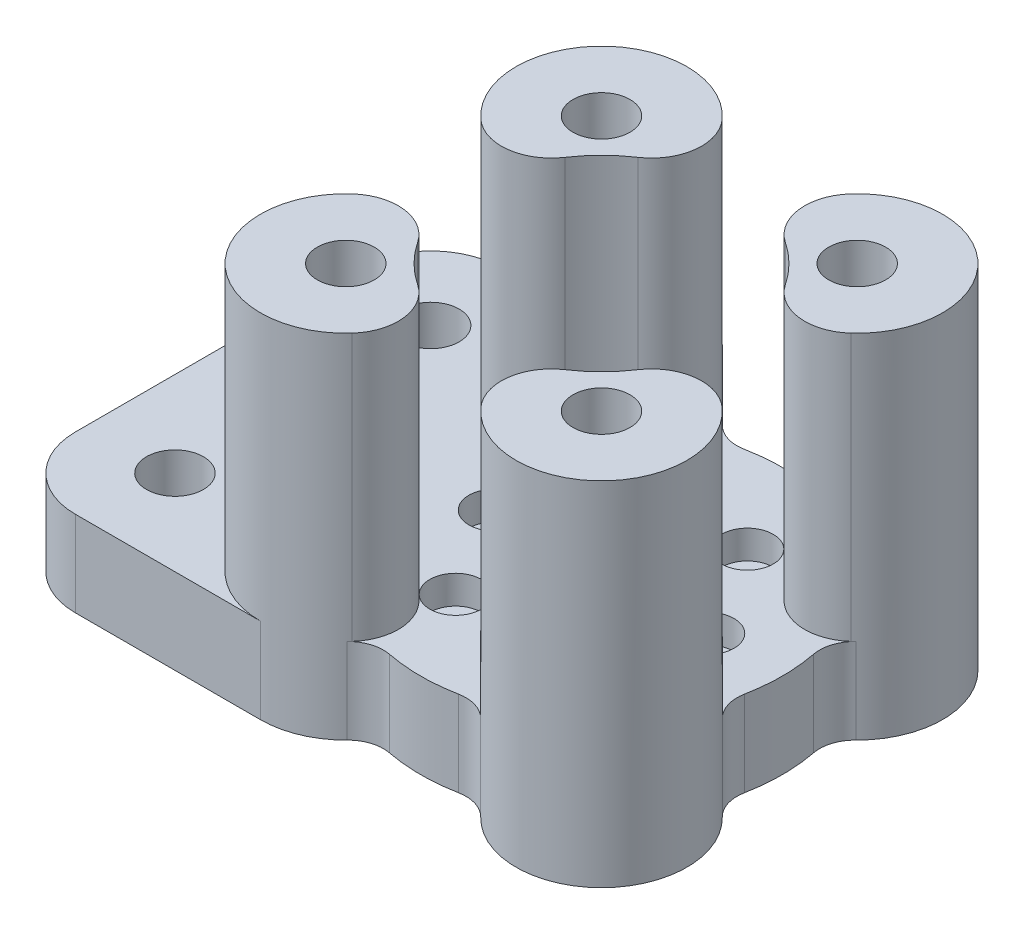
SolidWorks part; units mm, degrees
material "1060 Alloy"
ref_plane "Front" through (0, 0, 0) normal (0, 0, 1) x (1, 0, 0)
ref_plane "Top" through (0, 0, 0) normal (0, 1, 0) x (1, 0, 0)
ref_plane "Right" through (0, 0, 0) normal (1, 0, 0) x (0, 0, -1)
sketch "Sketch1" plane through (0, 0, 0) normal (0, 1, 0) x (1, 0, 0)
  line L0 (0, 0) -> (-17.9605, 17.9605) construction
  line L1 (0, 0) -> (0, 25.4) construction
  line L2 (0, 0) -> (-7.5, 12.9904) construction
  line L3 (-17.9605, 29.9605) -> (-43.9605, 29.9605)
  line L4 (-53.9605, 19.9605) -> (-53.9605, -19.9605)
  line L5 (-43.9605, -29.9605) -> (-17.9605, -29.9605)
  circle A0 centre (-17.9605, 17.9605) radius 4
  circle A1 centre (17.9605, 17.9605) radius 4
  circle A2 centre (17.9605, -17.9605) radius 4
  circle A3 centre (-17.9605, -17.9605) radius 4
  circle A4 centre (0, 0) radius 10.5
  arc A5 (-9.3775, 26.347) -> (-26.347, 9.3775) centre (-17.9605, 17.9605) ccw construction
  arc A6 (26.347, 9.3775) -> (9.3775, 26.347) centre (17.9605, 17.9605) ccw
  arc A7 (9.3775, -26.347) -> (26.347, -9.3775) centre (17.9605, -17.9605) ccw
  arc A8 (-26.347, -9.3775) -> (-9.3775, -26.347) centre (-17.9605, -17.9605) ccw construction
  arc A9 (-24.9332, 4.8471) -> (-24.9332, -4.8471) centre (0, 0) ccw construction
  arc A10 (-4.8471, -24.9332) -> (4.8471, -24.9332) centre (0, 0) ccw
  arc A11 (24.9332, -4.8471) -> (24.9332, 4.8471) centre (0, 0) ccw
  arc A12 (-4.8471, 24.9332) -> (-9.3775, 26.347) centre (-5.8013, 29.8413) cw
  arc A13 (4.8471, 24.9332) -> (-4.8471, 24.9332) centre (0, 0) ccw
  arc A14 (9.3775, 26.347) -> (4.8471, 24.9332) centre (5.8013, 29.8413) cw
  arc A15 (26.347, 9.3775) -> (24.9332, 4.8471) centre (29.8413, 5.8013) ccw
  arc A16 (24.9332, -4.8471) -> (26.347, -9.3775) centre (29.8413, -5.8013) ccw
  arc A17 (9.3775, -26.347) -> (4.8471, -24.9332) centre (5.8013, -29.8413) ccw
  arc A18 (-4.8471, -24.9332) -> (-9.3775, -26.347) centre (-5.8013, -29.8413) ccw
  arc A19 (-24.9332, -4.8471) -> (-26.347, -9.3775) centre (-29.8413, -5.8013) cw construction
  arc A20 (-24.9332, 4.8471) -> (-26.347, 9.3775) centre (-29.8413, 5.8013) ccw construction
  circle A21 centre (0, 0) radius 15 construction
  circle A22 centre (-7.5, 12.9904) radius 2
  circle A23 centre (7.5, 12.9904) radius 2
  circle A24 centre (15, 0) radius 2
  circle A25 centre (7.5, -12.9904) radius 2
  circle A26 centre (-7.5, -12.9904) radius 2
  circle A27 centre (-15, 0) radius 2
  arc A28 (-9.3775, 26.347) -> (-17.9605, 29.9605) centre (-17.9605, 17.9605) ccw
  arc A29 (-9.3775, -26.347) -> (-17.9605, -29.9605) centre (-17.9605, -17.9605) cw
  circle A30 centre (-41.9605, 17.9605) radius 4
  circle A31 centre (-41.9605, -17.9605) radius 4
  arc A32 (-53.9605, -19.9605) -> (-43.9605, -29.9605) centre (-43.9605, -19.9605) ccw
  arc A33 (-43.9605, 29.9605) -> (-53.9605, 19.9605) centre (-43.9605, 19.9605) ccw
  point P0 (0, 0)
  point P17 (0, 0)
  point P27 (0, 0)
  point P56 (0, 0)
  dimension "D5" = 8
  dimension "D6" = 21
  dimension "D1" = 5
  dimension "D7" = 12
  dimension "D9" = 30
  dimension "D11" = 4
  dimension "D14" = 10
  dimension "D3" = 25.4
  dimension "D2" = 12
  dimension "D10" = 12
  dimension "D13" = 24
  dimension "D4" = 4
  dimension "D8" = 4
  dimension "D12" = 6
extrude "base" add sketch "Sketch1" along normal blind 12
sketch "Sketch2" plane through (0, 12, 0) normal (0, 1, 0) x (1, 0, 0)
  circle A0 centre (0, 0) radius 15 construction
  circle A1 centre (-7.5, 12.9904) radius 3.625
  circle A2 centre (7.5, 12.9904) radius 3.625
  circle A3 centre (15, 0) radius 3.625
  circle A4 centre (7.5, -12.9904) radius 3.625
  circle A5 centre (-7.5, -12.9904) radius 3.625
  circle A7 centre (-15, 0) radius 3.625
  point P15 (0, 0)
  point P17 (0, 0)
  dimension "D1" = 7.25
  dimension "D2" = 6
extrude "bolt head recesses" cut sketch "Sketch2" against normal blind 4
sketch "Sketch3" plane through (0, 12, 0) normal (0, 1, 0) x (1, 0, 0)
  circle A0 centre (-17.9605, -17.9605) radius 4
  arc A1 (-17.6441, -5.9647) -> (-5.9647, -17.6441) centre (-17.9605, -17.9605) ccw
  circle A2 centre (-17.9605, -17.9605) radius 4 construction
  arc A4 (-5.9647, 17.6441) -> (-17.6441, 5.9647) centre (-17.9605, 17.9605) ccw
  circle A5 centre (-17.9605, 17.9605) radius 4
  arc A6 (17.6441, 5.9647) -> (5.9647, 17.6441) centre (17.9605, 17.9605) ccw
  circle A7 centre (17.9605, 17.9605) radius 4
  arc A8 (5.9647, -17.6441) -> (17.6441, -5.9647) centre (17.9605, -17.9605) ccw
  circle A9 centre (17.9605, -17.9605) radius 4
  circle A10 centre (0, 0) radius 25.4 construction
  arc A11 (-17.6441, -5.9647) -> (-5.9647, -17.6441) centre (0, 0) ccw
  circle A12 centre (-7.5, 12.9904) radius 3.625 construction
  arc A13 (-5.9647, 17.6441) -> (-17.6441, 5.9647) centre (0, 0) ccw
  arc A14 (17.6441, 5.9647) -> (5.9647, 17.6441) centre (0, 0) ccw
  arc A15 (5.9647, -17.6441) -> (17.6441, -5.9647) centre (0, 0) ccw
  arc A16 (-17.9605, -29.9605) -> (-9.3775, -26.347) centre (-17.9605, -17.9605) ccw construction
  point P21 (0, 0)
  dimension "D1" = 4
extrude "legs" add sketch "Sketch3" along normal blind 37.5
fillet "Fillet2" radius 7 8 edges at (-17.6441, 30.75, 5.9647) (-5.9647, 30.75, 17.6441) (17.6441, 30.75, 5.9647) (5.9647, 30.75, 17.6441) (17.6441, 30.75, -5.9647) (5.9647, 30.75, -17.6441) (-17.6441, 30.75, -5.9647) (-5.9647, 30.75, -17.6441)
sketch "Sketch4" plane through (0, 0, 0) normal (0, -1, 0) x (1, 0, 0)
  circle A0 centre (0, 0) radius 25.4 construction
  circle A1 centre (17.9605, 17.9605) radius 7
  circle A2 centre (17.9605, -17.9605) radius 7
  circle A3 centre (-17.9605, -17.9605) radius 7
  circle A4 centre (-17.9605, 17.9605) radius 7
  point P16 (0, 0)
  dimension "D1" = 14
  dimension "D2" = 4
extrude "m8 counterbore" cut sketch "Sketch4" against normal blind 8
equation "\"D3@Sketch1\"=\"square plate bolt pattern diameter\"/2"
equation "\"D1@base\" = \"motor mount plate thickness\""
equation "\"D5@Sketch1\"=\"square plate bolt hole ID\""
equation "\"D6@Sketch1\"=\"motor mount coupler hole diameter\""
equation "\"bearing OD\" = 30mm"
equation "\"bearing outer race thickness\"= 1mm"
equation "\"bearing ID\"= 10mm"
equation "\"bearing depth\"= 9mm"
equation "\"bearing inner race thickness\"= 1mm"
equation "\"small seal OD\" = 20mm"
equation "\"small seal ID\"= 8mm"
equation "\"small seal depth\" = 6mm"
equation "\"big seal OD\" = 30mm"
equation "\"big seal ID\"= 15mm"
equation "\"big seal depth\"= 8mm"
equation "\"z\" = 12"
equation "\"de\" = 0.426in"
equation "\"d2\" = 2.097in"
equation "\"d_exit\" =\"b2\""
equation "\"theta\" = 15"
equation "\"b2\" = .15in"
equation "\"b1\" = \"b2\" + (\"d2\"/2 - \"de\"/2)*sin(\"theta\")"
equation "\"s\" = ( 1/\"z\")*(3.14*\"de\" - (3.14*(\"de\"^2) / (4*(\"b1\"))))"
equation "\"s_opening\" = (3.14*\"de\" - \"z\"*\"s\")/\"z\""
equation "\"area_eye\"=3.14*(\"de\"^2)/4"
equation "\"single_channel_area\"=\"s_opening\"*\"b1\""
equation "\"impeller upper clearance\"= .5mm"
equation "\"impeller horizontal clearance\"= .5mm"
equation "\"impeller bottom clearance\"= .5mm"
equation "\"impeller base thickness\"= 2mm"
equation "\"impeller boss depth\" = 14mm"
equation "\"impeller boss diameter\" = \"big seal ID\""
equation "\"impeller dowel diameter\" = 2mm"
equation "\"impeller bolt head diameter\" = 7.5mm"
equation "\"impeller bolt head depth\" = 4mm"
equation "\"impeller shaft bore\"= 8mm"
equation "\"impeller shaft bore depth\" = \"impeller boss depth\" + \"impeller base thickness\" - \"impeller bolt head depth\" - 3mm"
equation "\"impeller dowel length\" = 2mm*2 + \"impeller shaft bore\""
equation "\"impeller screw hole bore\" = 4mm"
equation "\"shaft impeller screw hole diameter\" = \"impeller screw hole bore\""
equation "\"shaft impeller section length\" = \"impeller shaft bore depth\""
equation "\"shaft impeller screw hole depth\" = \"shaft impeller section length\"-\"impeller dowel diameter\"-2mm"
equation "\"shaft impeller section diameter\" = \"impeller shaft bore\""
equation "\"shaft seal section diameter\"=\"small seal ID\""
equation "\"shaft seal section length\"=\"small seal depth\" + 2mm"
equation "\"shaft bearing section diameter\" = \"bearing ID\""
equation "\"shaft bearing section length\" = \"bearing depth\""
equation "\"shaft bearing stop diameter\" = \"bearing ID\" + 2mm"
equation "\"shaft bearing stop length\" = 2mm"
equation "\"shaft coupler section diameter\" = 8mm"
equation "\"shaft coupler section length\" = \"shaft bearing stop length\" + \"coupler length\"/2 + 4mm"
equation "\"coupler motor shaft hole ID\"= 8mm"
equation "\"coupler OD\"= 17mm"
equation "\"coupler length\"= 25mm"
equation "\"square plate diameter\" = 3in"
equation "\"square plate bolt pattern diameter\"= 2in"
equation "\"square plate bolt hole ID\" = 8mm"
equation "\"bearing plate bearing stop ID\" = \"bearing OD\" - 4mm"
equation "\"bearing plate bearing stop depth\" = 3mm"
equation "\"bearing plate thickness\" = \"bearing depth\" + \"bearing plate bearing stop depth\""
equation "\"small seal plate lip depth\" = \"shaft bearing stop length\" + 1mm"
equation "\"small seal plate lip ID\" = \"small seal OD\" - 3mm"
equation "\"small seal plate thickness\" = \"small seal plate lip depth\" + \"small seal depth\""
equation "\"big seal plate lip depth\" = 3mm"
equation "\"big seal plate thickness\" = \"shaft bearing stop length\" + \"shaft seal section length\" + \"impeller boss depth\" - \"impeller bottom clearance\"-\"small seal plate thickness\""
equation "\"impeller cavity center height\"= \"impeller bottom clearance\" + \"impeller upper clearance\" + \"final impeller center height\""
equation "\"impeller cavity diameter\"= 2 * \"impeller horizontal clearance\" + \"d2\""
equation "\"impeller cavity outer height\"= \"impeller bottom clearance\" + \"impeller upper clearance\" + \"impeller base thickness\" + \"b2\""
equation "\"impeller housing bolt count\" = 8"
equation "\"impeller housing bolt diameter\" = 6mm"
equation "\"impeller housing bolt pattern diameter\" = 2.75in"
equation "\"impeller housing o-ring channel height\"= 1.5mm"
equation "\"impeller housing o ring channel width\"= 1.5mm"
equation "\"impeller housing o-ring diameter\" = 2in"
equation "\"impeller housing threaded inlet diameter\" = 14mm"
equation "\"impeller housing threaded inlet depth\"= 8mm"
equation "\"impeller housing thickness\"= \"impeller housing threaded inlet depth\" + \"impeller cavity center height\"+ 4mm"
equation "\"impeller housing exit threaded diameter\"= 8mm"
equation "\"impeller housing exit threaded depth\"= 8mm"
equation "\"impeller housing diameter\" = 3.5in"
equation "\"impeller housing diffuser conical angle\"=10"
equation "\"impeller housing diffuser tangent angle\"=20"
equation "\"impeller housing outlet purchase\" = 5mm"
equation "\"motor to housing distance\" = \"motor shaft pride\" + \"shaft coupler section length\" - \"bearing plate bearing stop depth\" + 2mm"
equation "\"motor mount coupler hole diameter\"= \"coupler OD\"+ 4mm"
equation "\"motor mount to housing post radius\"= ( 3 * \"square plate bolt hole ID\" ) / 2"
equation "\"motor mount m4 screw hole diameter\"= 4mm"
equation "\"motor mount m4 head diameter\"= 7.25mm"
equation "\"motor mount m4 head depth\"= 4mm"
equation "\"motor mount plate thickness\"= 8mm + \"motor mount m4 head depth\""
equation "\"motor shaft pride\"= 32mm"
equation "\"motor shaft flat section length from tip\"= 25.7mm"
equation "\"motor shaft bore end clearance\"= 2mm"
equation "\"coupler shaft to motor clearance\" = 2mm"
equation "\"motor mount shaft hole depth\"= \"motor shaft pride\""
equation "\"bit size\" = 2mm"
equation "\"inlet area before cut\" = \"bit size\" * (\"z\") * \"b1\""
equation "\"area to cut\" = \"inlet area before cut\" - \"area_eye\""
equation "\"height to cut\" = \"area to cut\" / ((\"z\")* \"bit size\")"
equation "\"final impeller center height\" = \"impeller base thickness\" + \"b1\" - \"height to cut\""
equation "\"D7@Sketch1\"=\"square plate bolt hole ID\"*3/2"
equation "\"motor mount m4 pattern diamater\" = 30mm"
equation "\"D9@Sketch1\"=\"motor mount m4 pattern diamater\""
equation "\"D11@Sketch1\"=\"motor mount m4 screw hole diameter\""
equation "\"D1@Sketch2\"=\"motor mount m4 head diameter\""
equation "\"D1@bolt head recesses\" = \"motor mount m4 head depth\""
equation "\"D1@legs\" = \"motor to housing distance\" - \"motor mount plate thickness\""
